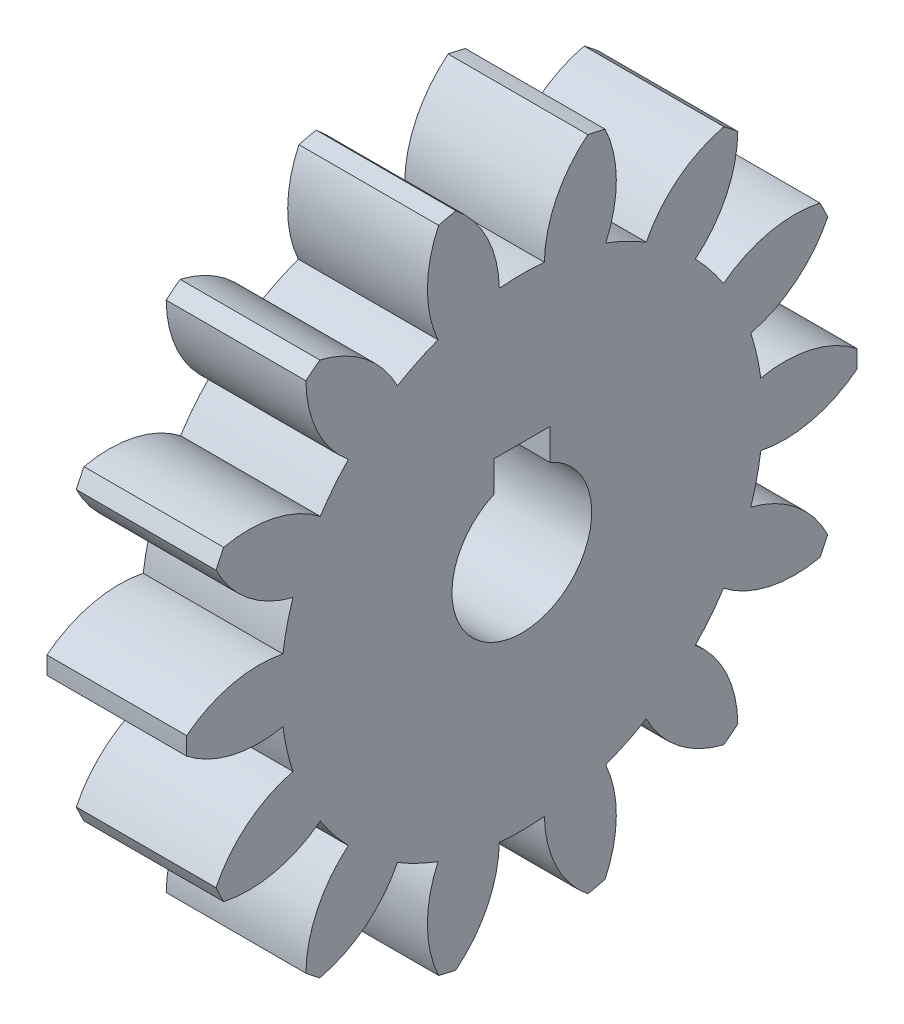
SolidWorks part; units mm, degrees
ref_plane "Plane1" through (0, 0, 0) normal (0, 0, 1) x (1, 0, 0)
ref_plane "Plane2" through (0, 0, 0) normal (0, 1, 0) x (1, 0, 0)
ref_plane "Plane3" through (0, 0, 0) normal (1, 0, 0) x (0, 0, -1)
sketch "HoldingSke" plane through (0, 0, 0) normal (0, 1, 0) x (1, 0, 0)
  line L0 (0, 0) -> (0.3234, -0.0806)
  line L1 (-15, 0) -> (100, 0) construction
  line L2 (0, 0) -> (-2.1039, 2.3779)
  line L3 (0, 0) -> (-11.863, 4.5341)
  line L4 (0, 0) -> (8.3795, 2.0892)
  line L5 (0, 0) -> (-46.8476, -17.4728)
  line L6 (0, 0) -> (-8.2896, -5.593)
  line L7 (-2.1039, 2.3779) -> (8.6586, 51.2059)
  line L8 (-76.2, 54.61) -> (-74.4, 54.61)
  line L9 (-71.009, 38.7566) -> (-53.1078, 45.2721)
  line L10 (-76.2, 71.12) -> (104.1128, 71.12)
  line L11 (0, 0) -> (-10, 0)
  line L12 (-76.2, 101.6) -> (-76.093, 101.6)
  line L13 (24.9733, 27.94) -> (52.9518, 28.4284)
  line L14 (24.9733, 27.94) -> (24.9743, 27.94)
  line L15 (24.9733, 27.94) -> (100.4006, 29.5858)
  line L16 (-63.627, -3) -> (-12.827, -3)
  circle A0 centre (0, 0) radius 5
  circle A1 centre (0, 0) radius 17.249
  circle A2 centre (0, 0) radius 37.5
  circle A3 centre (0, 0) radius 5
  dimension "MHD" = 34.498
  dimension "Hub_dia" = 75
  dimension "Bore" = 10
  dimension "MBD" = 10
  dimension "Num_teeth" = 14
  dimension "Pitch" = 0.3333
  dimension "Overall_len" = 50
  dimension "Show_teeth" = 14
  dimension "Thickness" = 10
  dimension "OAL" = 50.0001
  dimension "T_dim" = 1.8
  dimension "Ap" = 20
  dimension "H" = 19.05
  dimension "Pitch_radius" = 180.3128
  dimension "Width" = 10
  dimension "Backlash" = 0.107
  dimension "Addendum_fac" = 1
  dimension "Dedendum_fac" = 1.25
  dimension "Clearance_fac" = 0.25
  dimension "Dedendum_add" = 0.001
  dimension "Module" = 3
sketch "BasProSke" plane through (0, 0, 0) normal (0, 1, 0) x (1, 0, 0)
  line L0 (-10, 0) -> (60, 0) construction
  line L1 (0, 0) -> (0, 24)
  line L2 (0, 0) -> (10, 0)
  line L3 (10, 0) -> (10, 24)
  line L4 (10, 24) -> (0, 24)
  dimension "Thickness" = 10
  dimension "Diameter" = 48
revolve "Base-Revolve" add sketch "BasProSke" angle 360 about L0
sketch "TooCutSke" plane through (0, 0, 0) normal (1, 0, 0) x (0, 0, -1)
  line L1 (0, 0) -> (0, 107) construction
  line L2 (0, 0) -> (-2.5383, 20.846) construction
  line L3 (0, 0) -> (-9.2961, 40.729) construction
  line L4 (-2.5383, 20.846) -> (-4.6481, 20.3645) construction
  arc A0 (1.6111, 17.1736) -> (-1.6111, 17.1736) centre (0, 0) ccw
  arc A1 (4.745, 23.5522) -> (-4.745, 23.5522) centre (0, 0) ccw
  circle A2 centre (0, 0) radius 21 construction
  circle A3 centre (0, 0) radius 19.7335 construction
  arc A4 (-1.6111, 17.1736) -> (-4.745, 23.5522) centre (-10.0095, 17.0066) ccw
  arc A5 (4.745, 23.5522) -> (1.6111, 17.1736) centre (10.0095, 17.0066) ccw
  dimension "Root_dia" = 34.498
  dimension "Overcut_dia" = 48.0508
  dimension "Pitch_dia" = 42
  dimension "Base_dia" = 39.4671
  dimension "Flank_rad" = 8.4
  dimension "Half_ang" = 12.857
  dimension "Half_CT" = 2.164
extrude "ToothCut" cut sketch "TooCutSke" along normal through all
fillet "Breaks" [suppressed] radius 0.06
fillet "RootFillets" [suppressed] radius 0.751
pattern_circular "TeethCuts" count 14 every 25.714 about axis through (-10, 0, 0) along (1, 0, 0) of "ToothCut", "RootFillets", "Breaks"
sketch "HubNeaOneSke" plane through (0, 0, 0) normal (-1, 0, 0) x (0, 0, 1)
  circle A0 centre (0, 0) radius 17.249
  dimension "Diameter" = 34.498
extrude "HubNearOne" [suppressed] add sketch "HubNeaOneSke" along normal blind 40.0001
sketch "HubNeaBotSke" plane through (0, 0, 0) normal (-1, 0, 0) x (0, 0, 1)
  circle A0 centre (0, 0) radius 17.249
  dimension "Diameter" = 34.498
extrude "HubNearBoth" [suppressed] add sketch "HubNeaBotSke" along normal blind 20
ref_plane "FarPln" through (10, 0, 0) normal (1, 0, 0) x (0, 0, -1)
sketch "HubFarSke" plane through (10, 0, 0) normal (1, 0, 0) x (0, 0, -1)
  circle A0 centre (0, 0) radius 17.249
  dimension "Diameter" = 34.498
extrude "HubFar" [suppressed] add sketch "HubFarSke" along normal blind 20
sketch "BorSke" plane through (0, 0, 0) normal (1, 0, 0) x (0, 0, -1)
  circle A0 centre (0, 0) radius 5
  dimension "Diameter" = 10
extrude "Bore" cut sketch "BorSke" along normal mid plane 100.0001
sketch "KeySke" plane through (0, 0, 0) normal (1, 0, 0) x (0, 0, -1)
  line L0 (-2, 0) -> (-2, 6.8)
  line L1 (-2, 6.8) -> (2, 6.8)
  line L2 (2, 6.8) -> (2, 0)
  line L3 (0, 0) -> (0, 34) construction
  line L4 (-2, 0) -> (2, 0)
  dimension "Offset" = 6.8
  dimension "Width" = 4
extrude "Keyway" cut sketch "KeySke" along normal mid plane 100.0001
pattern_circular "Keyway2" [suppressed] count 2 every 90 about axis through (-10, 0, 0) along (1, 0, 0)
equation "' \"Module@HoldingSke\" = 6.35"
equation "' \"Num_teeth@HoldingSke\" = 12"
equation "' \"Ap@HoldingSke\" =  20"
equation "' \"Ap@HoldingSke\" = 20"
equation "' \"Width@HoldingSke\" = 0.5 * 25.4"
equation "' \"Hub_dia@HoldingSke\"= 1 * 25.4"
equation "' \"Hub_dia@HoldingSke\" = 1 * 25.4"
equation "' \"Overall_len@HoldingSke\" = 1.0 * 25.4"
equation "' \"Bore@HoldingSke\" = 0.75 * 25.4"
equation "' \"T_dim@HoldingSke\" = 0.1 * 25.4"
equation "' \"Width@KeySke\" = 0.25 * 25.4"
equation "' \"Show_teeth@HoldingSke\" = 13"
equation "' \"Backlash@HoldingSke\" = 0.009 * 25.4"
equation "' \"Addendum_fac@HoldingSke\" = 1.0"
equation "' \"Dedendum_fac@HoldingSke\" = 1.25"
equation "' \"Dedendum_add@HoldingSke\" = 0.00005 * 25.4"
equation "' \"Clearance_fac@HoldingSke\" = 0.25"
equation "\"Pitch@HoldingSke\" = 1 / \"Module@HoldingSke\""
equation "\"Overcut_dia@TooCutSke\" = (\"Num_teeth@HoldingSke\" + 2 * \"Addendum_fac@HoldingSke\") / \"Pitch@HoldingSke\" + 0.002 * 25.4"
equation "\"Pitch_dia@TooCutSke\" = \"Num_teeth@HoldingSke\" / \"Pitch@HoldingSke\""
equation "\"Base_dia@TooCutSke\" = \"Num_teeth@HoldingSke\" / \"Pitch@HoldingSke\" * cos((\"Ap@HoldingSke\"  * 3.14159265 / 180))"
equation "\"Root_dia@TooCutSke\" = (\"Num_teeth@HoldingSke\" + 2) / \"Pitch@HoldingSke\" - 2 * (\"Addendum_fac@HoldingSke\" + \"Dedendum_fac@HoldingSke\") / \"Pitch@HoldingSke\" - \"Dedendum_add@HoldingSke\" * 2"
equation "\"Half_ang@TooCutSke\" = 180 / \"Num_teeth@HoldingSke\""
equation "\"Half_CT@TooCutSke\" = \"Num_teeth@HoldingSke\" / \"Pitch@HoldingSke\" * sin((3.14159265 / 2 / \"Num_teeth@HoldingSke\")) / 2 - 7 * \"Backlash@HoldingSke\" / 4"
equation "\"Flank_rad@TooCutSke\" = \"Num_teeth@HoldingSke\" / \"Pitch@HoldingSke\" / 5"
equation "\"Radius@RootFillets\" = \"Clearance_fac@HoldingSke\" / \"Pitch@HoldingSke\" + \"Dedendum_add@HoldingSke\""
equation "\"Break_rad@Breaks\" = 0.02 / \"Pitch@HoldingSke\""
equation "\"Thickness@HoldingSke\" = \"Width@HoldingSke\""
equation "\"OAL@HoldingSke\" = \"Thickness@HoldingSke\""
equation "\"MHD@HoldingSke\" = (\"Num_teeth@HoldingSke\" + 2) / \"Pitch@HoldingSke\" - 2 * (\"Addendum_fac@HoldingSke\" + \"Dedendum_fac@HoldingSke\")  / \"Pitch@HoldingSke\" - \"Dedendum_add@HoldingSke\" * 2"
equation "\"MBD@HoldingSke\" = (\"Num_teeth@HoldingSke\" + 2) / \"Pitch@HoldingSke\" - 2 * (\"Addendum_fac@HoldingSke\" + \"Dedendum_fac@HoldingSke\")  / \"Pitch@HoldingSke\" - \"Dedendum_add@HoldingSke\" * 2 - 0.002 * 25.4"
equation "\"MHD@HoldingSke\" = ((sgn( \"MHD@HoldingSke\" - \"Hub_dia@HoldingSke\" )-1)*( \"MHD@HoldingSke\" - \"Hub_dia@HoldingSke\" ))/-2+ \"Hub_dia@HoldingSke\""
equation "\"MBD@HoldingSke\" = ((sgn( \"MBD@HoldingSke\" - \"Bore@HoldingSke\" )-1)*( \"MBD@HoldingSke\" - \"Bore@HoldingSke\" ))/-2+ \"Bore@HoldingSke\""
equation "\"OAL@HoldingSke\" = ((sgn( \"OAL@HoldingSke\" - \"Overall_len@HoldingSke\" )+1)*( \"OAL@HoldingSke\" - \"Overall_len@HoldingSke\" ))/2 + \"Overall_len@HoldingSke\" + 0.000002 * 25.4"
equation "\"Num_teeth@TeethCuts\" = int( \"Show_teeth@HoldingSke\" ) + 1"
equation "\"Num_teeth@TeethCuts\" = ((sgn( \"Num_teeth@TeethCuts\" - \"Num_teeth@HoldingSke\" )-1)*( \"Num_teeth@TeethCuts\" - \"Num_teeth@HoldingSke\" ))/-2+ \"Num_teeth@HoldingSke\""
equation "\"Num_teeth@TeethCuts\" = ((sgn( \"Num_teeth@TeethCuts\" - 2.0)+1)*( \"Num_teeth@TeethCuts\" - 2.0))/2 +2.0"
equation "\"Angle@TeethCuts\" = 360.0 / \"Num_teeth@HoldingSke\""
equation "\"Diameter@BasProSke\" = (\"Num_teeth@HoldingSke\" + 2 * \"Addendum_fac@HoldingSke\") / \"Pitch@HoldingSke\""
equation "\"Thickness@BasProSke\"  = \"Thickness@HoldingSke\""
equation "' \"Fillet_rad@BasProSke\" =  \"Thickness@HoldingSke\" * 0.05"
equation "' \"Fillet_rad@BasProSke\" = \"Thickness@HoldingSke\" * 0.05"
equation "\"MHD@HoldingSke\" = ((sgn( \"MHD@HoldingSke\" - \"Root_dia@TooCutSke\" )-1)*( \"MHD@HoldingSke\" - \"Root_dia@TooCutSke\" ))/-2+ \"Root_dia@TooCutSke\""
equation "\"Diameter@HubNeaOneSke\" = \"MHD@HoldingSke\""
equation "\"Length@HubNearOne\" = \"OAL@HoldingSke\" - \"Thickness@BasProSke\""
equation "\"Diameter@HubNeaBotSke\" = \"MHD@HoldingSke\""
equation "\"Length@HubNearBoth\" = ( \"OAL@HoldingSke\" - \"Thickness@BasProSke\" ) / 2.0"
equation "\"Thickness@FarPln\" = \"Thickness@BasProSke\""
equation "\"Diameter@HubFarSke\" = \"MHD@HoldingSke\""
equation "\"Length@HubFar\" = ( \"OAL@HoldingSke\" - \"Thickness@BasProSke\" ) / 2.0"
equation "\"Diameter@BorSke\" = \"MBD@HoldingSke\""
equation "\"D1@Bore\" = \"OAL@HoldingSke\" * 2.0"
equation "\"D1@Keyway\" = \"OAL@HoldingSke\" * 2.0"
equation "\"Offset@KeySke\" = \"T_dim@HoldingSke\" + \"MBD@HoldingSke\" / 2.0"
